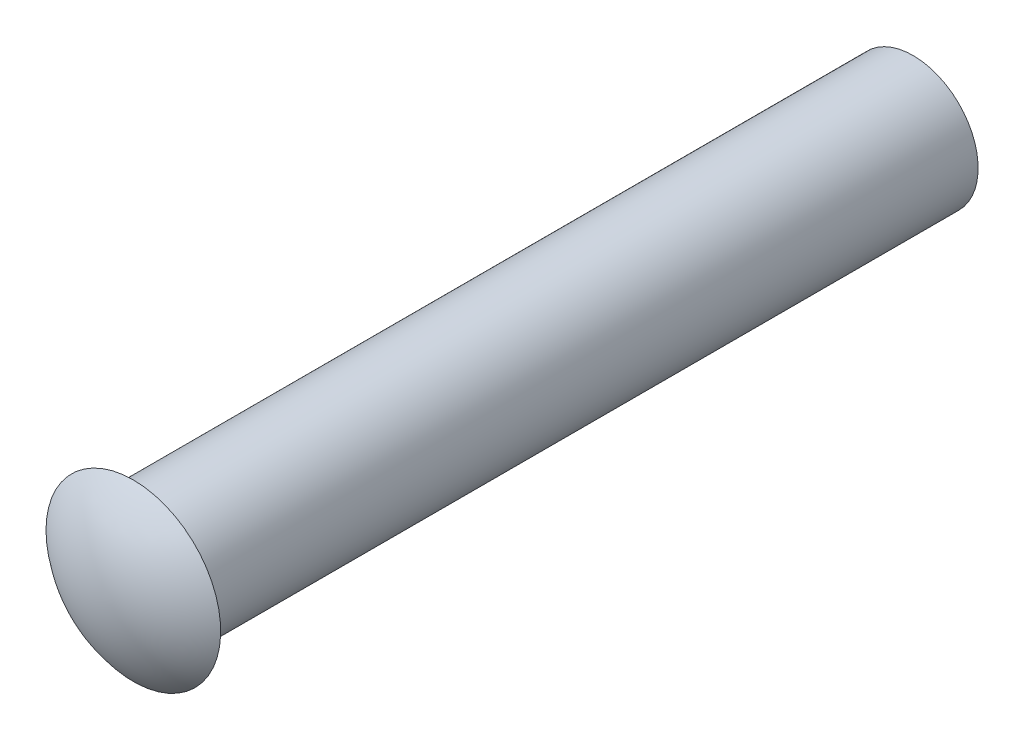
SolidWorks part; units mm, degrees
material "Chrome Stainless Steel"
ref_plane "Front Plane" through (0, 0, 0) normal (0, 0, 1) x (1, 0, 0)
ref_plane "Top Plane" through (0, 0, 0) normal (0, 1, 0) x (1, 0, 0)
ref_plane "Right Plane" through (0, 0, 0) normal (1, 0, 0) x (0, 0, -1)
sketch "Sketch1" plane through (0, 0, 0) normal (1, 0, 0) x (0, 0, -1)
  line L0 (19.8374, 0) -> (0, 0)
  line L1 (0.7874, 2.1336) -> (0.7874, 1.5875)
  line L2 (0.7874, 1.5875) -> (19.8374, 1.5875)
  line L3 (19.8374, 1.5875) -> (19.8374, 0)
  arc A0 (0, 0) -> (0.7874, 2.1336) centre (3.2844, 0) cw
  point P5 (1.5347, 5.3081)
  dimension "D1" = 1.5875
  dimension "D2" = 19.05
  dimension "D3" = 0.7874
  dimension "D4" = 2.1336
revolve "Revolve1" add sketch "Sketch1" angle 360 about L0
